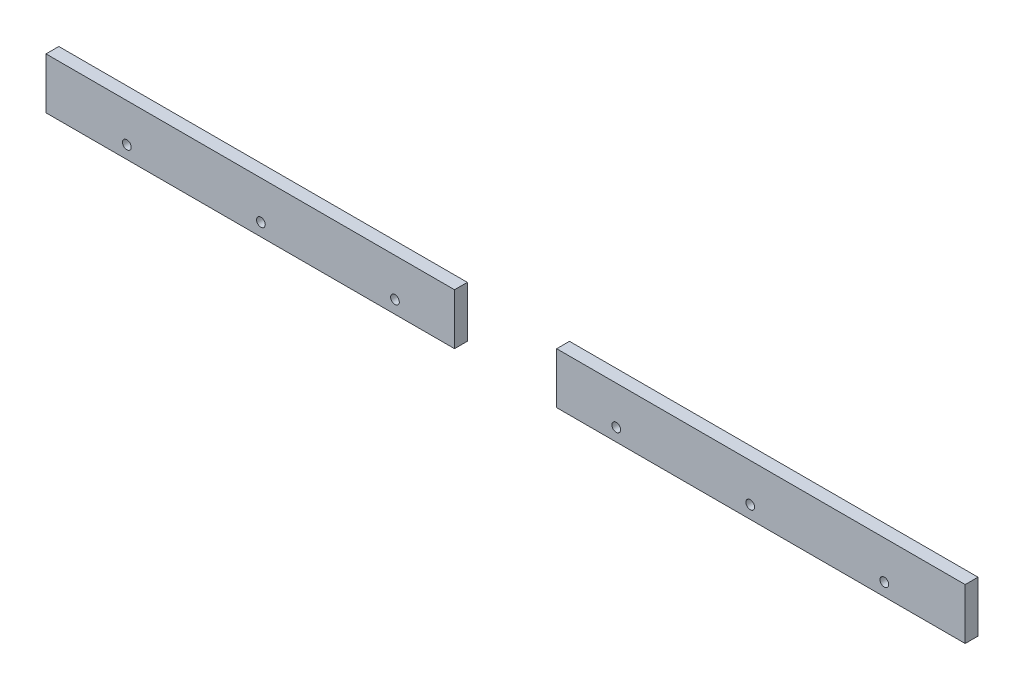
SolidWorks part; units mm, degrees
ref_plane "Front Plane" through (0, 0, 0) normal (0, 0, 1) x (1, 0, 0)
ref_plane "Top Plane" through (0, 0, 0) normal (0, 1, 0) x (1, 0, 0)
ref_plane "Right Plane" through (0, 0, 0) normal (1, 0, 0) x (0, 0, -1)
sketch "Sketch1" plane through (0, 0, 0) normal (0, 0, 1) x (1, 0, 0)
  line L1 (-342.9, -19.05) -> (342.9, -19.05)
  line L2 (-342.9, -19.05) -> (-342.9, 19.05)
  line L3 (-342.9, 19.05) -> (342.9, 19.05)
  line L4 (342.9, -19.05) -> (342.9, 19.05)
  line L5 (-342.9, -19.05) -> (342.9, 19.05) construction
  line L6 (-342.9, 19.05) -> (342.9, -19.05) construction
  point P0 (0, 0)
  dimension "D1" = 685.8
  dimension "D2" = 38.1
extrude "Boss-Extrude1" add sketch "Sketch1" along normal blind 9.5631
sketch "Sketch2" plane through (0, 0, 9.5631) normal (0, 0, 1) x (1, 0, 0)
  line L0 (-342.9, -19.05) -> (-342.9, -9.525) construction
  line L1 (-342.9, 19.05) -> (-342.9, -19.05) construction
  line L2 (-342.9, -9.525) -> (-282.575, -9.525) construction
  line L4 (-282.575, -9.525) -> (-182.5625, -9.525) construction
  line L5 (-182.5625, -9.525) -> (-82.55, -9.525) construction
  line L6 (-342.9, 19.05) -> (-38.1, 19.05) construction
  line L7 (342.9, 19.05) -> (-342.9, 19.05) construction
  line L13 (342.9, 19.05) -> (38.1, 19.05) construction
  circle A0 centre (-282.575, -9.525) radius 3.25
  circle A1 centre (-182.5625, -9.525) radius 3.25
  circle A2 centre (-82.55, -9.525) radius 3.25
  point P15 (0, 0)
  point P24 (34.5598, 19.05)
  dimension "D3" = 6.5
  dimension "D1" = 9.525
  dimension "D2" = 60.325
  dimension "D4" = 100.0125
  dimension "D5" = 100.0125
  dimension "D6" = 304.8
  dimension "D7" = 304.8
extrude "Cut-Extrude1" cut sketch "Sketch2" against normal blind 9.5631
ref_plane "Plane1" through (0, 0, 0) normal (-1, 0, 0) x (0, 0, 1)
mirror "Mirror1" about plane through (0, 0, 0) normal (-1, 0, 0) of "Cut-Extrude1"
sketch "Sketch4" plane through (0, 0, 9.5631) normal (0, 0, 1) x (1, 0, 0)
  line L0 (-342.9, 19.05) -> (-38.1, 19.05) construction
  line L1 (342.9, 19.05) -> (-342.9, 19.05) construction
  line L2 (342.9, 19.05) -> (38.1, 19.05) construction
  line L3 (-342.9, -19.05) -> (342.9, -19.05) construction
  line L4 (-38.1, 19.05) -> (38.1, 19.05)
  line L5 (-38.1, 19.05) -> (-38.1, -19.05)
  line L6 (-38.1, -19.05) -> (38.1, -19.05)
  line L7 (38.1, 19.05) -> (38.1, -19.05)
  dimension "D1" = 304.8
extrude "Cut-Extrude2" cut sketch "Sketch4" against normal blind 9.5631
